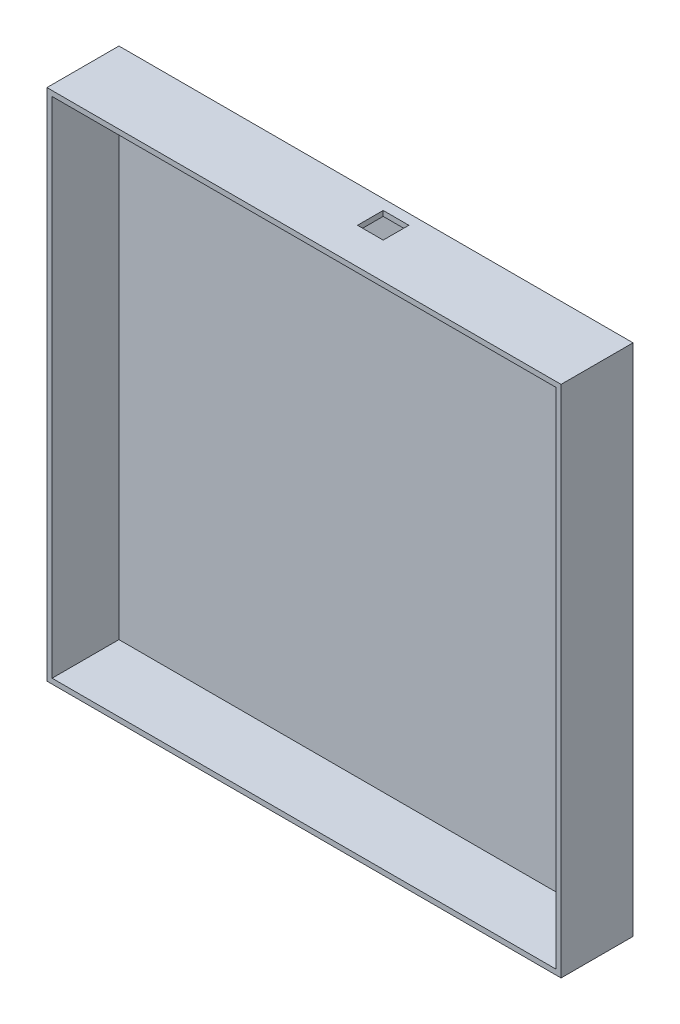
SolidWorks part; units mm, degrees
ref_plane "Front Plane" through (0, 0, 0) normal (0, 0, 1) x (1, 0, 0)
ref_plane "Top Plane" through (0, 0, 0) normal (0, 1, 0) x (1, 0, 0)
ref_plane "Right Plane" through (0, 0, 0) normal (1, 0, 0) x (0, 0, -1)
sketch "Sketch1" plane through (0, 0, 0) normal (0, 0, 1) x (1, 0, 0)
  line L0 (-49, 49) -> (-49, -49)
  line L1 (-50, 50) -> (50, 50)
  line L2 (-50, 50) -> (-50, -50)
  line L3 (-50, -50) -> (50, -50)
  line L4 (50, 50) -> (50, -50)
  line L5 (-50, 50) -> (50, -50) construction
  line L6 (-50, -50) -> (50, 50) construction
  line L7 (-49, -49) -> (49, -49)
  line L8 (49, 49) -> (49, -49)
  line L9 (-49, 49) -> (49, 49)
  point P0 (0, 0)
  dimension "D1" = 100
  dimension "D2" = 100
  dimension "D3" = 1
extrude "Boss-Extrude1" add sketch "Sketch1" along normal blind 13
sketch "Sketch2" plane through (0, 0, 0) normal (0, 0, -1) x (-1, 0, 0)
  line L4 (-50, 50) -> (-50, -50)
  line L5 (-50, -50) -> (50, -50)
  line L6 (50, -50) -> (50, 50)
  line L7 (50, 50) -> (-50, 50)
  line L8 (-50, 50) -> (-50, -50)
  line L9 (-50, -50) -> (50, -50)
  line L10 (50, -50) -> (50, 50)
  line L11 (50, 50) -> (-50, 50)
  dimension "D1" = 0
extrude "Boss-Extrude2" add sketch "Sketch2" along normal blind 1
sketch "Sketch3" plane through (0, 50, 0) normal (0, 1, 0) x (1, 0, 0)
  line L0 (-50, 1) -> (50, 1) construction
  line L1 (3.4, -1) -> (8.4, -1)
  line L2 (3.4, -1) -> (3.4, -6)
  line L3 (3.4, -6) -> (8.4, -6)
  line L4 (8.4, -1) -> (8.4, -6)
  line L5 (3.4, -1) -> (8.4, -6) construction
  line L6 (3.4, -6) -> (8.4, -1) construction
  line L7 (50, -13) -> (50, 1) construction
  point P0 (5.9, -3.5)
  dimension "D1" = 2
  dimension "D2" = 41.6
  dimension "D3" = 5
  dimension "D4" = 5
extrude "Cut-Extrude1" cut sketch "Sketch3" against normal blind 2
